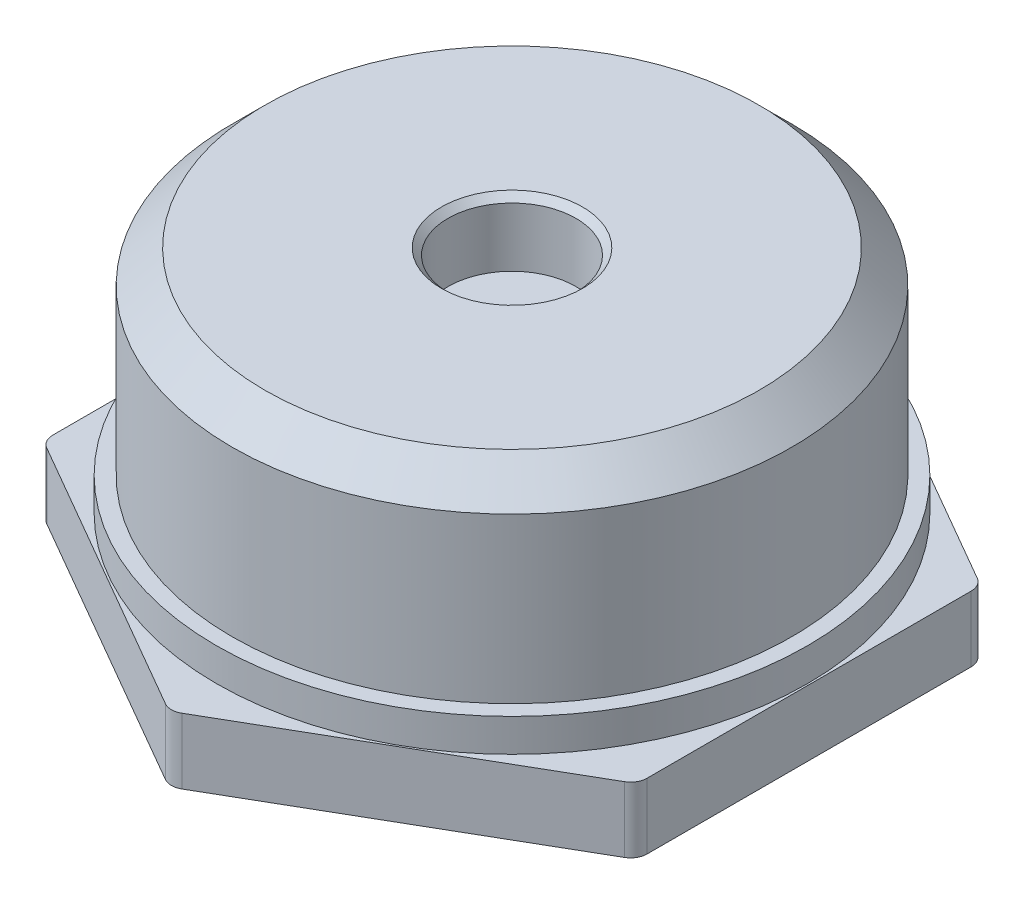
SolidWorks part; units mm, degrees
material "ABS"
ref_plane "Front Plane" through (0, 0, 0) normal (0, 0, 1) x (1, 0, 0)
ref_plane "Top Plane" through (0, 0, 0) normal (0, 1, 0) x (1, 0, 0)
ref_plane "Right Plane" through (0, 0, 0) normal (1, 0, 0) x (0, 0, -1)
ref_plane "Plane2" through (0, 31, 0) normal (0, 1, 0) x (1, 0, 0)
sketch "Sketch1" plane through (0, 31, 0) normal (0, 1, 0) x (1, 0, 0)
  line L1 (0, 10.45) -> (-9.05, 5.225)
  line L2 (-9.05, 5.225) -> (-9.05, -5.225)
  line L3 (-9.05, -5.225) -> (0, -10.45)
  line L4 (0, -10.45) -> (9.05, -5.225)
  line L5 (9.05, -5.225) -> (9.05, 5.225)
  line L6 (9.05, 5.225) -> (0, 10.45)
  circle A0 centre (0, 0) radius 9.05 construction
  dimension "D1" = 18.1
extrude "Boss-Extrude1" add sketch "Sketch1" along normal blind 2
fillet "Fillet1" radius 0.5 6 edges at (0, 32, -10.45) (-9.05, 32, -5.225) (-9.05, 32, 5.225) (0, 32, 10.45) (9.05, 32, 5.225) (9.05, 32, -5.225)
sketch "Sketch2" plane through (0, 33, 0) normal (0, 1, 0) x (1, 0, 0)
  circle A1 centre (0, 0) radius 9
  dimension "D2" = 18
extrude "Boss-Extrude2" add sketch "Sketch2" along normal blind 1 contours A1
sketch "Sketch3" plane through (0, 34, 0) normal (0, 1, 0) x (1, 0, 0)
  circle A0 centre (0, 0) radius 8.525
  dimension "D1" = 17.05
extrude "Boss-Extrude3" add sketch "Sketch3" along normal blind 4
sketch "Sketch4" plane through (0, 38, 0) normal (0, 1, 0) x (1, 0, 0)
  line L1 (0, 2.8868) -> (-2.5, 1.4434)
  line L2 (-2.5, 1.4434) -> (-2.5, -1.4434)
  line L3 (-2.5, -1.4434) -> (0, -2.8868)
  line L4 (0, -2.8868) -> (2.5, -1.4434)
  line L5 (2.5, -1.4434) -> (2.5, 1.4434)
  line L6 (2.5, 1.4434) -> (0, 2.8868)
  circle A0 centre (0, 0) radius 2.5 construction
  dimension "D1" = 5
extrude "Cut-Extrude1" cut sketch "Sketch4" against normal through all
sketch "Sketch5" plane through (0, 38, 0) normal (0, 1, 0) x (1, 0, 0)
  circle A0 centre (0, 0) radius 8.525
  circle A1 centre (0, 0) radius 8.525 construction
extrude "Boss-Extrude4" add sketch "Sketch5" along normal blind 1 and the other way blind 1
sketch "Sketch6" plane through (0, 39, 0) normal (0, 1, 0) x (1, 0, 0)
  circle A1 centre (0, 0) radius 8.525
  circle A2 centre (0, 0) radius 8.525 construction
extrude "Boss-Extrude5" add sketch "Sketch6" along normal blind 1
chamfer "Chamfer2" distance 1 angle 45 1 edges at (0, 40, 8.525)
sketch "Sketch7" plane through (0, 40, 0) normal (0, 1, 0) x (1, 0, 0)
  circle A0 centre (0, 0) radius 1.95
  dimension "D1" = 3.9
extrude "Cut-Extrude2" cut sketch "Sketch7" against normal blind 2
chamfer "Chamfer3" distance 0.2 angle 45 1 edges at (0, 40, 1.95)
